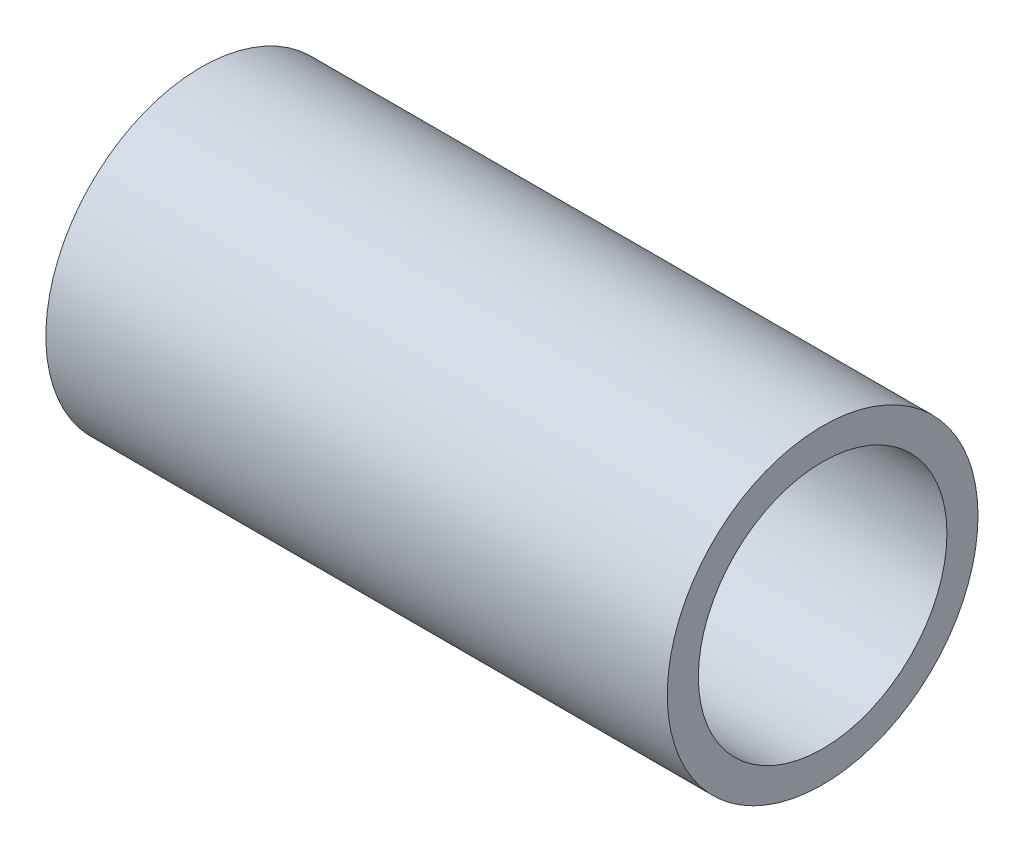
SolidWorks part; units mm, degrees
ref_plane "Front Plane" through (0, 0, 0) normal (0, 0, 1) x (1, 0, 0)
ref_plane "Top Plane" through (0, 0, 0) normal (0, 1, 0) x (1, 0, 0)
ref_plane "Right Plane" through (0, 0, 0) normal (1, 0, 0) x (0, 0, -1)
sketch "Sketch1" plane through (0, 0, 0) normal (1, 0, 0) x (0, 0, -1)
  circle A0 centre (0, 0) radius 6.35
  circle A1 centre (0, 0) radius 7.9375
extrude "Boss-Extrude1" add sketch "Sketch1" along normal blind 31.75
